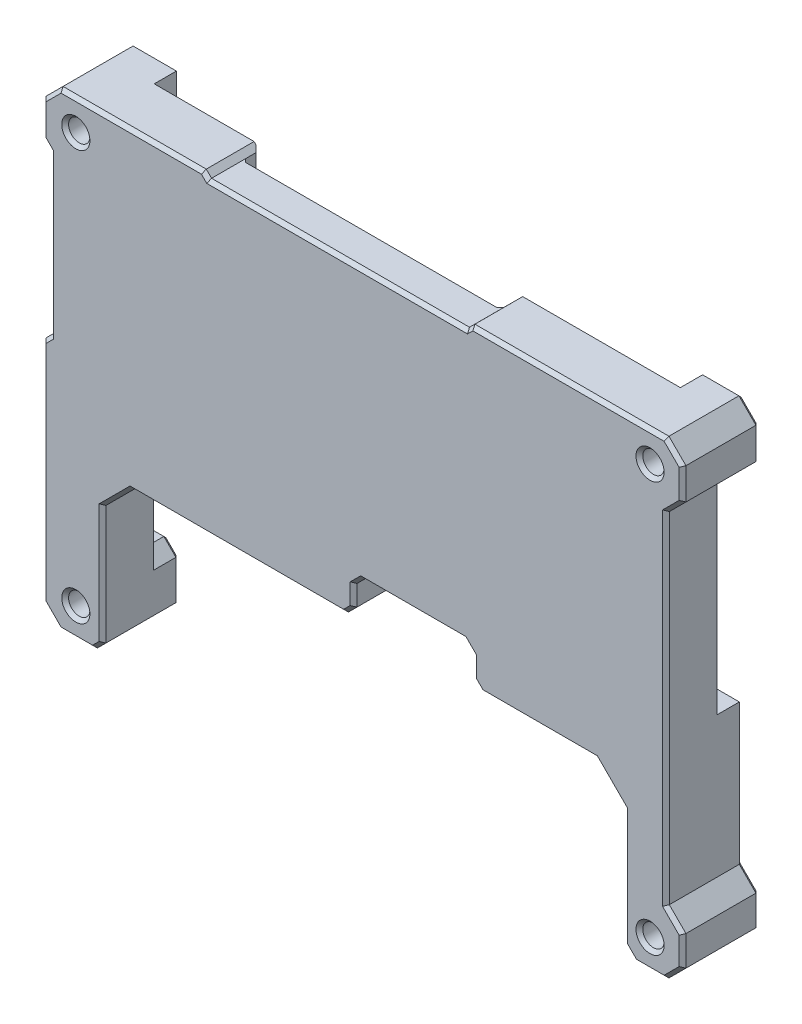
SolidWorks part; units mm, degrees
ref_plane "前视基准面" through (0, 0, 0) normal (0, 0, 1) x (1, 0, 0)
ref_plane "上视基准面" through (0, 0, 0) normal (0, 1, 0) x (1, 0, 0)
ref_plane "右视基准面" through (0, 0, 0) normal (1, 0, 0) x (0, 0, -1)
other "Configuration Table"
sketch "草图1" plane through (0, 0, 0) normal (0, 0, 1) x (1, 0, 0)
  line L1 (0, 0) -> (85, 0)
  line L2 (0, 0) -> (0, 65)
  line L3 (0, 65) -> (85, 65)
  line L4 (85, 0) -> (85, 65)
  dimension "D1" = 65
  dimension "D2" = 85
extrude "凸台-拉伸1" add sketch "草图1" along normal blind 10
sketch "草图2" plane through (0, 0, 0) normal (0, 0, -1) x (-1, 0, 0)
  circle A0 centre (-76.1669, 56.4425) radius 1.25
  circle A1 centre (-8.8888, 56.4425) radius 1.25
  circle A2 centre (-76.1669, 8.4151) radius 1.25
  circle A3 centre (-8.8888, 8.4151) radius 1.25
  dimension "D1" = 2.5
  dimension "D2" = 2.5
  dimension "D3" = 2.5
  dimension "D4" = 2.5
extrude "切除-拉伸1" cut sketch "草图2" against normal up to next
sketch "草图3" plane through (0, 0, 0) normal (0, 0, -1) x (-1, 0, 0)
  line L28 (-85, 0) -> (-85, 65) construction
  line L29 (-85, 65) -> (0, 65)
  line L30 (-85, 65) -> (-85, 0)
  line L31 (-85, 0) -> (0, 0)
  line L32 (0, 65) -> (0, 0)
  line L56 (-5, 33.4629) -> (-5.8713, 34.3342)
  line L57 (-5, 6.9926) -> (-5, 33.4629)
  line L58 (-6.9926, 5) -> (-5, 6.9926)
  line L59 (-16.2697, 5) -> (-6.9926, 5)
  line L60 (-17.4616, 6.1866) -> (-16.2697, 5)
  line L61 (-31.7436, 6.1829) -> (-17.4616, 6.1866)
  line L62 (-32.9265, 5) -> (-31.7436, 6.1829)
  line L63 (-58.7727, 5) -> (-32.9265, 5)
  line L64 (-60.0435, 6.2655) -> (-58.7727, 5)
  line L65 (-73.1524, 6.2618) -> (-60.0435, 6.2655)
  line L66 (-74.4142, 5) -> (-73.1524, 6.2618)
  line L67 (-77.9822, 5) -> (-74.4142, 5)
  line L68 (-79.9747, 6.9926) -> (-77.9822, 5)
  line L69 (-79.9747, 10.5083) -> (-79.9747, 6.9926)
  line L70 (-78.0283, 12.46) -> (-79.9747, 10.5083)
  line L71 (-78.032, 52.3531) -> (-78.0283, 12.46)
  line L72 (-79.9747, 54.2958) -> (-78.032, 52.3531)
  line L73 (-79.9747, 57.9821) -> (-79.9747, 54.2958)
  line L74 (-77.9822, 59.9747) -> (-79.9747, 57.9821)
  line L75 (-55.2451, 59.9747) -> (-77.9822, 59.9747)
  line L76 (-54.6148, 59.3497) -> (-55.2451, 59.9747)
  line L77 (-24.3949, 59.3534) -> (-54.6148, 59.3497)
  line L78 (-23.7736, 59.9747) -> (-24.3949, 59.3534)
  line L79 (-6.9926, 59.9747) -> (-23.7736, 59.9747)
  line L80 (-5, 57.9821) -> (-6.9926, 59.9747)
  line L81 (-5, 54.0174) -> (-5, 57.9821)
  line L82 (-5.875, 53.1371) -> (-5, 54.0174)
  line L83 (-5.8713, 34.3342) -> (-5.875, 53.1371)
extrude "切除-拉伸2" cut sketch "草图3" against normal up to next
sketch "草图4" plane through (0, 0, 0) normal (0, 0, -1) x (-1, 0, 0)
  line L0 (-73.1524, 6.2618) -> (-73.1524, 20.0323)
  line L1 (-73.1524, 20.0323) -> (-69.8316, 23.3532)
  line L2 (-69.8316, 23.3532) -> (-46.788, 23.3532)
  line L3 (-46.788, 23.3532) -> (-15.4038, 23.3532)
  line L4 (-15.4038, 23.3532) -> (-12.014, 19.9634)
  line L5 (-12.014, 19.9634) -> (-12.014, 6.188)
  line L6 (-31.7436, 6.1829) -> (-17.4616, 6.1866) construction
  line L7 (-12.014, 6.188) -> (-12.014, 0.194)
  line L8 (-12.014, 0.194) -> (-73.1524, 0.194)
  line L9 (-73.1524, 0.194) -> (-73.1524, 6.2618)
  line L10 (-73.1524, 6.2618) -> (-60.0435, 6.2655) construction
  dimension "D1" = 135
  dimension "D2" = 135
  dimension "D3" = 4.7938
extrude "切除-拉伸4" cut sketch "草图4" against normal up to next
sketch "草图5" plane through (0, 0, 0) normal (0, 0, -1) x (-1, 0, 0)
  line L0 (-24.3949, 59.3534) -> (-24.3949, 53.9064)
  line L1 (-24.3949, 53.9064) -> (-25.5261, 52.7749)
  line L2 (-25.5261, 52.7749) -> (-53.4826, 52.7749)
  line L3 (-53.4826, 52.7749) -> (-54.6142, 53.9061)
  line L4 (-54.6142, 53.9061) -> (-54.6148, 59.3497)
  line L5 (-24.3949, 59.3534) -> (-54.6148, 59.3497) construction
  line L6 (-23.7736, 59.9747) -> (-24.3949, 59.3534) construction
  line L7 (-24.3949, 59.3534) -> (-54.6148, 59.3497)
  dimension "D1" = 135
  dimension "D2" = 134.993
  dimension "D3" = 1.6
  dimension "D4" = 1.6
extrude "切除-拉伸7" cut sketch "草图5" against normal blind 6
sketch "草图6" plane through (0, 0, 0) normal (0, 0, -1) x (-1, 0, 0)
  line L0 (-5.8713, 34.3342) -> (-11.6713, 34.3342)
  line L1 (-5, 33.4629) -> (-5.8713, 34.3342) construction
  line L6 (-5.8713, 34.3342) -> (-5.875, 53.1371) construction
  line L7 (-5.8735, 45.2504) -> (-5.8745, 50.3342)
  line L8 (-5.8735, 45.2504) -> (-5.8713, 34.3342)
  line L9 (-5.8745, 50.3342) -> (-11.6713, 50.3342)
  line L10 (-11.6713, 50.3342) -> (-11.6713, 34.3342)
  dimension "D1" = 5.8
  dimension "D2" = 16
extrude "切除-拉伸8" cut sketch "草图6" against normal blind 6
sketch "草图7" plane through (0, 0, 0) normal (0, 0, -1) x (-1, 0, 0)
  line L0 (-76.4321, 51.2623) -> (-74.4321, 51.2623)
  line L1 (-74.4321, 51.2623) -> (-71.3195, 54.3749)
  line L2 (-71.3195, 54.3749) -> (-71.3195, 58.3749)
  line L3 (-71.3195, 58.3749) -> (-71.3195, 59.9747)
  line L4 (-76.4321, 51.2623) -> (-78.0319, 51.2623)
  line L5 (-78.0298, 28.9377) -> (-75.0298, 28.9377)
  line L6 (-75.0298, 28.9377) -> (-75.0298, 13.9377)
  line L7 (-72.9158, 11.8236) -> (-75.0298, 13.9377)
  line L8 (-24.3949, 57.6633) -> (-23.7321, 57.6633)
  line L9 (-23.7321, 57.6633) -> (-23.0617, 58.334)
  line L10 (-23.0617, 58.334) -> (-12.072, 58.334)
  line L11 (-12.072, 58.334) -> (-12.072, 55.334)
  line L12 (-12.072, 55.334) -> (-9.875, 53.1371)
  line L13 (-9.875, 53.1371) -> (-5.875, 53.1371)
  line L14 (-6.5998, 12.014) -> (-10.5998, 12.014)
  line L15 (-10.5998, 12.014) -> (-12.014, 10.5998)
  line L16 (-12.014, 10.5998) -> (-12.014, 5)
  line L17 (-6.5998, 12.014) -> (-5, 12.014)
  line L18 (-72.9158, 11.8236) -> (-73.1524, 12.0603)
  line L37 (-5.8713, 34.3342) -> (-11.6713, 34.3342)
  line L38 (-11.6713, 34.3342) -> (-11.6713, 50.3342)
  line L39 (-11.6713, 34.3342) -> (-11.6713, 50.3342)
  line L40 (-11.6713, 50.3342) -> (-5.8745, 50.3342)
  line L41 (-11.6713, 50.3342) -> (-5.8745, 50.3342)
  line L42 (-5.8745, 50.3342) -> (-5.875, 53.1371)
  line L43 (-5.875, 53.1371) -> (-5, 54.0174)
  line L44 (-5, 54.0174) -> (-5, 57.9821)
  line L45 (-5, 57.9821) -> (-6.9926, 59.9747)
  line L46 (-6.9926, 59.9747) -> (-23.7736, 59.9747)
  line L47 (-23.7736, 59.9747) -> (-24.3949, 59.3534)
  line L48 (-24.3949, 59.3534) -> (-24.3949, 53.9064)
  line L49 (-24.3949, 53.9064) -> (-25.5261, 52.7749)
  line L50 (-25.5261, 52.7749) -> (-53.4826, 52.7749)
  line L51 (-53.4826, 52.7749) -> (-54.6142, 53.9061)
  line L52 (-54.6142, 53.9061) -> (-54.6148, 59.3497)
  line L53 (-54.6148, 59.3497) -> (-55.2451, 59.9747)
  line L54 (-55.2451, 59.9747) -> (-77.9822, 59.9747)
  line L55 (-77.9822, 59.9747) -> (-79.9747, 57.9821)
  line L56 (-79.9747, 57.9821) -> (-79.9747, 54.2958)
  line L57 (-79.9747, 54.2958) -> (-78.032, 52.3531)
  line L58 (-78.032, 52.3531) -> (-78.0283, 12.46)
  line L59 (-78.0283, 12.46) -> (-79.9747, 10.5083)
  line L60 (-79.9747, 10.5083) -> (-79.9747, 6.9926)
  line L61 (-79.9747, 6.9926) -> (-77.9822, 5)
  line L62 (-77.9822, 5) -> (-74.4142, 5)
  line L63 (-74.4142, 5) -> (-73.1524, 6.2618)
  line L64 (-73.1524, 6.2618) -> (-73.1524, 20.0323)
  line L65 (-73.1524, 20.0323) -> (-69.8316, 23.3532)
  line L66 (-69.8316, 23.3532) -> (-15.4038, 23.3532)
  line L67 (-15.4038, 23.3532) -> (-12.014, 19.9634)
  line L68 (-12.014, 19.9634) -> (-12.014, 5)
  line L70 (-12.014, 5) -> (-6.9926, 5)
  line L71 (-6.9926, 5) -> (-5, 6.9926)
  line L72 (-5, 6.9926) -> (-5, 33.4629)
  line L73 (-5, 33.4629) -> (-5.8713, 34.3342)
  line L74 (-5.8713, 34.3342) -> (-11.6713, 34.3342)
  line L79 (-5.8745, 50.3342) -> (-5.875, 53.1371)
  line L80 (-5.875, 53.1371) -> (-5, 54.0174)
  line L81 (-5, 54.0174) -> (-5, 57.9821)
  line L82 (-5, 57.9821) -> (-6.9926, 59.9747)
  line L83 (-6.9926, 59.9747) -> (-23.7736, 59.9747)
  line L84 (-23.7736, 59.9747) -> (-24.3949, 59.3534)
  line L85 (-24.3949, 59.3534) -> (-24.3949, 53.9064)
  line L86 (-24.3949, 53.9064) -> (-25.5261, 52.7749)
  line L87 (-25.5261, 52.7749) -> (-53.4826, 52.7749)
  line L88 (-53.4826, 52.7749) -> (-54.6142, 53.9061)
  line L89 (-54.6142, 53.9061) -> (-54.6148, 59.3497)
  line L90 (-54.6148, 59.3497) -> (-55.2451, 59.9747)
  line L91 (-55.2451, 59.9747) -> (-77.9822, 59.9747)
  line L92 (-77.9822, 59.9747) -> (-79.9747, 57.9821)
  line L93 (-79.9747, 57.9821) -> (-79.9747, 54.2958)
  line L94 (-79.9747, 54.2958) -> (-78.032, 52.3531)
  line L95 (-78.032, 52.3531) -> (-78.0283, 12.46)
  line L96 (-78.0283, 12.46) -> (-79.9747, 10.5083)
  line L97 (-79.9747, 10.5083) -> (-79.9747, 6.9926)
  line L98 (-79.9747, 6.9926) -> (-77.9822, 5)
  line L99 (-77.9822, 5) -> (-74.4142, 5)
  line L100 (-74.4142, 5) -> (-73.1524, 6.2618)
  line L101 (-73.1524, 6.2618) -> (-73.1524, 20.0323)
  line L102 (-73.1524, 20.0323) -> (-69.8316, 23.3532)
  line L103 (-69.8316, 23.3532) -> (-15.4038, 23.3532)
  line L104 (-15.4038, 23.3532) -> (-12.014, 19.9634)
  line L105 (-12.014, 19.9634) -> (-12.014, 5)
  line L107 (-12.014, 5) -> (-6.9926, 5)
  line L108 (-6.9926, 5) -> (-5, 6.9926)
  line L109 (-5, 6.9926) -> (-5, 33.4629)
  line L110 (-5, 33.4629) -> (-5.8713, 34.3342)
  dimension "D2" = 90
  dimension "D3" = 15
  dimension "D4" = 135
  dimension "D5" = 4
  dimension "D6" = 3
  dimension "D7" = 135
  dimension "D8" = 45
  dimension "D9" = 3
  dimension "D1" = 0
extrude "切除-拉伸11" cut sketch "草图7" against normal blind 4
sketch "草图8" plane through (0, 0, 4) normal (0, 0, -1) x (-1, 0, 0)
  line L1 (-73.3481, 45.9587) -> (-65.3481, 45.9587)
  line L2 (-73.3481, 45.9587) -> (-73.3481, 40.9587)
  line L3 (-73.3481, 40.9587) -> (-65.3481, 40.9587)
  line L4 (-65.3481, 45.9587) -> (-65.3481, 40.9587)
  dimension "D1" = 5
  dimension "D2" = 8
extrude "切除-拉伸12" cut sketch "草图8" against normal blind 1
sketch "草图10" plane through (0, 0, 4) normal (0, 0, -1) x (-1, 0, 0)
  line L0 (-41.5465, 34.8898) -> (-37.5465, 34.8898)
  line L1 (-46.9465, 34.8898) -> (-41.5465, 34.8898)
  line L2 (-46.9465, 34.8898) -> (-46.9465, 28.8898)
  line L3 (-46.9465, 28.8898) -> (-41.5465, 28.8898)
  line L4 (-41.5465, 34.8898) -> (-41.5465, 28.8898)
  line L5 (-37.5465, 34.8898) -> (-32.1465, 34.8898)
  line L6 (-37.5465, 34.8898) -> (-37.5465, 28.8898)
  line L7 (-37.5465, 28.8898) -> (-32.1465, 28.8898)
  line L8 (-32.1465, 34.8898) -> (-32.1465, 28.8898)
  line L9 (-37.5465, 28.8898) -> (-41.5465, 28.8898)
  dimension "D1" = 5.4
  dimension "D2" = 6
  dimension "D3" = 5.4
  dimension "D4" = 4
extrude "凸台-拉伸2" add sketch "草图10" along normal offset from surface (2.04 mm away) 3 contours L4 L1 L2 L3 | L9 L6 L0 L4 | L8 L5 L6 L7
sketch "草图11" plane through (0, 0, 4) normal (0, 0, -1) x (-1, 0, 0)
  line L1 (-40.8318, 43.6929) -> (-36.6318, 43.6929)
  line L2 (-40.8318, 43.6929) -> (-40.8318, 38.6929)
  line L3 (-40.8318, 38.6929) -> (-36.6318, 38.6929)
  line L4 (-36.6318, 43.6929) -> (-36.6318, 38.6929)
  dimension "D1" = 4.2
  dimension "D2" = 5
extrude "凸台-拉伸3" add sketch "草图11" along normal offset from surface (1.3001 mm away) 3
sketch "草图12" plane through (0, 0, 4) normal (0, 0, -1) x (-1, 0, 0)
  line L0 (-24.6106, 30.6859) -> (-32.1465, 34.8898)
  line L1 (-30.6106, 30.6859) -> (-18.6106, 30.6859)
  line L2 (-30.6106, 30.6859) -> (-30.6106, 24.6859)
  line L3 (-30.6106, 24.6859) -> (-18.6106, 24.6859)
  line L4 (-18.6106, 30.6859) -> (-18.6106, 24.6859)
  line L5 (-32.1465, 34.8898) -> (-46.9465, 34.8898) construction
  line L6 (-32.1465, 28.8898) -> (-32.1465, 34.8898) construction
  line L7 (-32.1465, 34.8898) -> (-32.1465, 28.8898)
  line L8 (-32.1465, 28.8898) -> (-30.6106, 27.6859)
  line M47 (-32.1465, 34.8898) -> (-32.1465, 28.8898)
  dimension "D1" = 12
  dimension "D2" = 6
extrude "凸台-拉伸4" add sketch "草图12" along normal up to surface (2.04 mm away) contours L4 L1 L2 L3 | L8 L2 L1 L0 M47 up to face at (39.5465, 31.8898, 1.96)
sketch "草图13" plane through (0, 0, 4) normal (0, 0, -1) x (-1, 0, 0)
  line L1 (-62.8902, 40.6188) -> (-59.7758, 40.6188)
  line L2 (-62.8902, 40.6188) -> (-62.8902, 35.6362)
  line L3 (-62.8902, 35.6362) -> (-59.7758, 35.6362)
  line L4 (-59.7758, 40.6188) -> (-59.7758, 35.6362)
extrude "凸台-拉伸5" add sketch "草图13" along normal blind 2
sketch "草图15" plane through (0, 0, 10) normal (0, 0, 1) x (1, 0, 0)
  line L0 (69.8316, 23.3532) -> (15.4038, 23.3532) construction
  line L1 (41.4288, 23.3532) -> (55.4288, 23.3532)
  line L2 (41.4288, 23.3532) -> (41.4288, 27.7532)
  line L3 (41.4288, 27.7532) -> (55.4288, 27.7532)
  line L4 (55.4288, 23.3532) -> (55.4288, 27.7532)
  dimension "D1" = 14
  dimension "D2" = 4.4
extrude "切除-拉伸13" cut sketch "草图15" against normal up to surface (6 mm away) up to face at (69.3481, 43.4587, 4)
chamfer "倒角1" distance 1 angle 45 5 edges at (12.014, 5, 5) (55.4288, 23.3532, 7) (55.4288, 27.7532, 7) (41.4288, 27.7532, 7) (41.4288, 23.3532, 7)
chamfer "倒角2" distance 0.6 angle 45 4 edges at (59.7758, 38.1275, 4) (61.333, 40.6188, 4) (62.8902, 38.1275, 4) (61.333, 35.6362, 4)
chamfer "倒角5" distance 0.6 angle 45 4 edges at (36.6318, 41.1929, 4) (38.7318, 38.6929, 4) (40.8318, 41.1929, 4) (38.7318, 43.6929, 4)
sketch "草图16" plane through (0, 0, 4) normal (0, 0, -1) x (-1, 0, 0)
  circle A0 centre (-17.8941, 26.9463) radius 1.6
  dimension "D1" = 3.2
extrude "切除-拉伸14" [suppressed] cut sketch "草图16" against normal through all both and the other way through all
sketch "草图17" plane through (0, 0, 0) normal (0, 0, -1) x (-1, 0, 0)
  line L0 (-12.072, 58.334) -> (-12.072, 59.9747)
  line L2 (-6.9926, 59.9747) -> (-23.7736, 59.9747) construction
  line L15 (-24.3949, 59.3534) -> (-24.3949, 57.6633)
  line L16 (-24.3949, 57.6633) -> (-23.7321, 57.6633)
  line L17 (-23.7321, 57.6633) -> (-23.0617, 58.334)
  line L18 (-23.0617, 58.334) -> (-12.072, 58.334)
  line L19 (-12.072, 58.334) -> (-12.072, 55.334)
  line L20 (-12.072, 55.334) -> (-9.875, 53.1371)
  line L21 (-9.875, 53.1371) -> (-5.875, 53.1371)
  line L22 (-5.875, 53.1371) -> (-5, 54.0174)
  line L23 (-5, 54.0174) -> (-5, 57.9821)
  line L24 (-5, 57.9821) -> (-6.9926, 59.9747)
  line L25 (-6.9926, 59.9747) -> (-23.7736, 59.9747)
  line L26 (-23.7736, 59.9747) -> (-24.3949, 59.3534)
  line L27 (-24.3949, 59.3534) -> (-24.3949, 57.6633)
  line L28 (-24.3949, 57.6633) -> (-23.7321, 57.6633)
  line L29 (-23.7321, 57.6633) -> (-23.0617, 58.334)
  line L30 (-23.0617, 58.334) -> (-12.072, 58.334)
  line L31 (-12.072, 58.334) -> (-12.072, 55.334)
  line L32 (-12.072, 55.334) -> (-9.875, 53.1371)
  line L33 (-9.875, 53.1371) -> (-5.875, 53.1371)
  line L34 (-5.875, 53.1371) -> (-5, 54.0174)
  line L35 (-5, 54.0174) -> (-5, 57.9821)
  line L36 (-5, 57.9821) -> (-6.9926, 59.9747)
  line L37 (-6.9926, 59.9747) -> (-23.7736, 59.9747)
  line L38 (-23.7736, 59.9747) -> (-24.3949, 59.3534)
  line M15 (-24.3949, 59.3534) -> (-24.3949, 57.6633)
  line M16 (-24.3949, 57.6633) -> (-23.7321, 57.6633)
  line M17 (-23.7321, 57.6633) -> (-23.0617, 58.334)
  line M18 (-23.0617, 58.334) -> (-12.072, 58.334)
  line M25 (-6.9926, 59.9747) -> (-23.7736, 59.9747)
  line M26 (-23.7736, 59.9747) -> (-24.3949, 59.3534)
  dimension "D1" = 0
extrude "切除-拉伸15" cut sketch "草图17" against normal up to surface (4 mm away) contours L0 M18 M25 M26 M15 M16 M17 up to face at (38.7318, 41.1929, 4)
sketch "草图18" plane through (0, 0, 0) normal (0, 0, -1) x (-1, 0, 0)
  line L0 (-73.7195, 59.9747) -> (-73.7195, 54.0502)
  line L1 (-71.3195, 59.9747) -> (-77.9822, 59.9747) construction
  line L2 (-73.7195, 54.0502) -> (-75.4166, 52.3531)
  line L3 (-75.4166, 52.3531) -> (-78.032, 52.3531)
  line L12 (-78.032, 52.3531) -> (-78.0319, 51.2623)
  line L13 (-78.0319, 51.2623) -> (-74.4321, 51.2623)
  line L14 (-74.4321, 51.2623) -> (-71.3195, 54.3749)
  line L15 (-71.3195, 54.3749) -> (-71.3195, 59.9747)
  line L16 (-71.3195, 59.9747) -> (-77.9822, 59.9747)
  line L17 (-77.9822, 59.9747) -> (-79.9747, 57.9821)
  line L18 (-79.9747, 57.9821) -> (-79.9747, 54.2958)
  line L19 (-79.9747, 54.2958) -> (-78.032, 52.3531)
  line L20 (-78.032, 52.3531) -> (-78.0319, 51.2623)
  line L21 (-78.0319, 51.2623) -> (-74.4321, 51.2623)
  line L22 (-74.4321, 51.2623) -> (-71.3195, 54.3749)
  line L23 (-71.3195, 54.3749) -> (-71.3195, 59.9747)
  line L24 (-71.3195, 59.9747) -> (-77.9822, 59.9747)
  line L25 (-77.9822, 59.9747) -> (-79.9747, 57.9821)
  line L26 (-79.9747, 57.9821) -> (-79.9747, 54.2958)
  line L27 (-79.9747, 54.2958) -> (-78.032, 52.3531)
  line M13 (-78.032, 52.3531) -> (-78.0319, 51.2623)
  line M14 (-78.0319, 51.2623) -> (-74.4321, 51.2623)
  line M15 (-74.4321, 51.2623) -> (-71.3195, 54.3749)
  line M16 (-71.3195, 54.3749) -> (-71.3195, 59.9747)
  line M17 (-71.3195, 59.9747) -> (-77.9822, 59.9747)
  dimension "D1" = 0
  dimension "D2" = 2.4
  dimension "D3" = 2.4
extrude "切除-拉伸16" cut sketch "草图18" against normal up to surface (4 mm away) contours L2 L3 L0 M13 M14 M15 M16 M17 up to face at (38.7318, 41.1929, 4)
chamfer "倒角6" distance 0.4 angle 45 39 edges at (5.9963, 5.9963, 10) (5, 20.2277, 10) (5.4357, 33.8986, 10) (5.8732, 43.7356, 10) (5.4375, 53.5772, 10) (5, 55.9998, 10) (5.9963, 58.9784, 10) (15.3831, 59.9747, 10) (24.0842, 59.6641, 10) (39.5048, 59.3515, 10) (54.93, 59.6622, 10) (66.6136, 59.9747, 10) (78.9785, 58.9784, 10) (79.9747, 56.139, 10) (79.0034, 53.3245, 10) (78.0302, 32.4066, 10) (79.0015, 11.4841, 10) (79.9747, 8.7504, 10) (78.9785, 5.9963, 10) (76.1982, 5, 10) (73.7833, 5.6309, 10) (73.1524, 13.1471, 10) (71.492, 21.6927, 10) (27.9163, 23.3532, 10) (55.9288, 23.8532, 10) (55.4288, 25.5532, 10) (54.9288, 27.2532, 10) (48.4288, 27.7532, 10) (41.9288, 27.2532, 10) (41.4288, 25.5532, 10) (40.9288, 23.8532, 10) (13.7089, 21.6583, 10) (12.014, 12.9817, 10) (11.514, 5.5, 10) (9.0033, 5, 10) (7.6388, 56.4425, 10) (74.9169, 8.4151, 10) (7.6388, 8.4151, 10) (74.9169, 56.4425, 10)
chamfer "倒角8" distance 0.4 angle 45 8 edges at (8.7729, 50.3342, 6) (11.6713, 50.3342, 5) (11.6713, 42.3342, 6) (8.7713, 34.3342, 6) (11.6713, 34.3342, 5) (8.7729, 50.3342, 4) (11.6713, 42.3342, 4) (8.7713, 34.3342, 4)
chamfer "倒角9" distance 0.4 angle 45 10 edges at (54.6145, 56.6279, 4) (54.6145, 56.6279, 6) (54.0484, 53.3405, 4) (54.0484, 53.3405, 6) (24.3949, 56.6299, 4) (24.3949, 56.6299, 6) (24.9605, 53.3407, 4) (24.9605, 53.3407, 6) (39.5044, 52.7749, 4) (39.5044, 52.7749, 6)
sketch "草图19" plane through (0, 0, 4) normal (0, 0, -1) x (-1, 0, 0)
  line L1 (-67.6316, 31.7532) -> (-58.2316, 31.7532)
  line L2 (-67.6316, 31.7532) -> (-67.6316, 23.3532)
  line L3 (-67.6316, 23.3532) -> (-58.2316, 23.3532)
  line L4 (-58.2316, 31.7532) -> (-58.2316, 23.3532)
  line L5 (-69.8316, 23.3532) -> (-56.4288, 23.3532) construction
  dimension "D1" = 9.4
  dimension "D2" = 8.4
  dimension "D3" = 2.2
extrude "切除-拉伸17" cut sketch "草图19" against normal blind 2.4
chamfer "倒角12" distance 0.4 angle 45 11 edges at (67.6316, 27.5532, 6.4) (67.6316, 23.3532, 5.2) (62.9316, 31.7532, 6.4) (67.6316, 31.7532, 5.2) (58.2316, 27.5532, 6.4) (58.2316, 31.7532, 5.2) (62.9316, 23.3532, 6.4) (58.2316, 23.3532, 5.2) (67.6316, 27.5532, 4) (58.2316, 27.5532, 4) (62.9316, 31.7532, 4)
chamfer "倒角13" [suppressed] distance 0.4
chamfer "倒角15" distance 0.4 angle 45 9 edges at (46.9465, 31.8898, 4) (39.5465, 34.8898, 4) (28.3786, 32.7879, 4) (21.6106, 30.6859, 4) (18.6106, 27.6859, 4) (24.6106, 24.6859, 4) (30.6106, 26.1859, 4) (31.3786, 28.2879, 4) (39.5465, 28.8898, 4)
sketch "草图20" plane through (0, 0, 0) normal (0, 0, -1) x (-1, 0, 0)
  line L0 (-6.9926, 59.9747) -> (-12.072, 59.9747) construction
  line L1 (-12.072, 59.9747) -> (-12.072, 55.334) construction
  line L2 (-12.072, 55.334) -> (-9.875, 53.1371) construction
  line L3 (-9.875, 53.1371) -> (-5.875, 53.1371) construction
  line L4 (-5.875, 53.1371) -> (-5, 54.0174) construction
  line L5 (-5, 54.0174) -> (-5, 57.9821) construction
  line L6 (-5, 57.9821) -> (-6.9926, 59.9747) construction
  line L7 (-73.7195, 54.0502) -> (-73.7195, 59.9747) construction
  line L8 (-73.7195, 59.9747) -> (-77.9822, 59.9747) construction
  line L9 (-77.9822, 59.9747) -> (-79.9747, 57.9821) construction
  line L10 (-79.9747, 57.9821) -> (-79.9747, 54.2958) construction
  line L11 (-79.9747, 54.2958) -> (-78.032, 52.3531) construction
  line L12 (-78.032, 52.3531) -> (-75.4166, 52.3531) construction
  line L13 (-75.4166, 52.3531) -> (-73.7195, 54.0502) construction
  line L14 (-73.1524, 6.2618) -> (-73.1524, 12.0603) construction
  line L15 (-73.1524, 12.0603) -> (-75.0298, 13.9377) construction
  line L16 (-75.0298, 13.9377) -> (-75.0298, 28.9377) construction
  line L17 (-75.0298, 28.9377) -> (-78.0298, 28.9377) construction
  line L18 (-78.0298, 28.9377) -> (-78.0283, 12.46) construction
  line L19 (-78.0283, 12.46) -> (-79.9747, 10.5083) construction
  line L20 (-79.9747, 10.5083) -> (-79.9747, 6.9926) construction
  line L21 (-79.9747, 6.9926) -> (-77.9822, 5) construction
  line L22 (-77.9822, 5) -> (-74.4142, 5) construction
  line L23 (-74.4142, 5) -> (-73.1524, 6.2618) construction
  line L24 (-12.014, 10.5998) -> (-12.014, 6) construction
  line L25 (-12.014, 6) -> (-11.014, 5) construction
  line L26 (-11.014, 5) -> (-6.9926, 5) construction
  line L27 (-6.9926, 5) -> (-5, 6.9926) construction
  line L28 (-5, 6.9926) -> (-5, 12.014) construction
  line L29 (-5, 12.014) -> (-10.5998, 12.014) construction
  line L30 (-10.5998, 12.014) -> (-12.014, 10.5998) construction
  line L31 (-6.9926, 59.9747) -> (-12.072, 59.9747)
  line L32 (-12.072, 59.9747) -> (-12.072, 55.334)
  line L33 (-12.072, 55.334) -> (-9.875, 53.1371)
  line L34 (-9.875, 53.1371) -> (-5.875, 53.1371)
  line L35 (-5.875, 53.1371) -> (-5, 54.0174)
  line L36 (-5, 54.0174) -> (-5, 57.9821)
  line L37 (-5, 57.9821) -> (-6.9926, 59.9747)
  line L38 (-73.7195, 54.0502) -> (-73.7195, 59.9747)
  line L39 (-73.7195, 59.9747) -> (-77.9822, 59.9747)
  line L40 (-77.9822, 59.9747) -> (-79.9747, 57.9821)
  line L41 (-79.9747, 57.9821) -> (-79.9747, 54.2958)
  line L42 (-79.9747, 54.2958) -> (-78.032, 52.3531)
  line L43 (-78.032, 52.3531) -> (-75.4166, 52.3531)
  line L44 (-75.4166, 52.3531) -> (-73.7195, 54.0502)
  line L45 (-73.1524, 6.2618) -> (-73.1524, 12.0603)
  line L46 (-73.1524, 12.0603) -> (-75.0298, 13.9377)
  line L47 (-75.0298, 13.9377) -> (-75.0298, 28.9377)
  line L48 (-75.0298, 28.9377) -> (-78.0298, 28.9377)
  line L49 (-78.0298, 28.9377) -> (-78.0283, 12.46)
  line L50 (-78.0283, 12.46) -> (-79.9747, 10.5083)
  line L51 (-79.9747, 10.5083) -> (-79.9747, 6.9926)
  line L52 (-79.9747, 6.9926) -> (-77.9822, 5)
  line L53 (-77.9822, 5) -> (-74.4142, 5)
  line L54 (-74.4142, 5) -> (-73.1524, 6.2618)
  line L55 (-12.014, 10.5998) -> (-12.014, 6)
  line L56 (-12.014, 6) -> (-11.014, 5)
  line L57 (-11.014, 5) -> (-6.9926, 5)
  line L58 (-6.9926, 5) -> (-5, 6.9926)
  line L59 (-5, 6.9926) -> (-5, 12.014)
  line L60 (-5, 12.014) -> (-10.5998, 12.014)
  line L61 (-10.5998, 12.014) -> (-12.014, 10.5998)
  line L62 (-6.9926, 59.9747) -> (-12.072, 59.9747)
  line L63 (-12.072, 59.9747) -> (-12.072, 55.334)
  line L64 (-12.072, 55.334) -> (-9.875, 53.1371)
  line L65 (-9.875, 53.1371) -> (-5.875, 53.1371)
  line L66 (-5.875, 53.1371) -> (-5, 54.0174)
  line L67 (-5, 54.0174) -> (-5, 57.9821)
  line L68 (-5, 57.9821) -> (-6.9926, 59.9747)
  line L69 (-12.014, 10.5998) -> (-12.014, 6)
  line L70 (-12.014, 6) -> (-11.014, 5)
  line L71 (-11.014, 5) -> (-6.9926, 5)
  line L72 (-6.9926, 5) -> (-5, 6.9926)
  line L73 (-5, 6.9926) -> (-5, 12.014)
  line L74 (-5, 12.014) -> (-10.5998, 12.014)
  line L75 (-10.5998, 12.014) -> (-12.014, 10.5998)
  line L76 (-73.1524, 6.2618) -> (-73.1524, 12.0603)
  line L77 (-73.1524, 12.0603) -> (-75.0298, 13.9377)
  line L78 (-75.0298, 13.9377) -> (-75.0298, 28.9377)
  line L79 (-75.0298, 28.9377) -> (-78.0298, 28.9377)
  line L80 (-78.0298, 28.9377) -> (-78.0283, 12.46)
  line L81 (-78.0283, 12.46) -> (-79.9747, 10.5083)
  line L82 (-79.9747, 10.5083) -> (-79.9747, 6.9926)
  line L83 (-79.9747, 6.9926) -> (-77.9822, 5)
  line L84 (-77.9822, 5) -> (-74.4142, 5)
  line L85 (-74.4142, 5) -> (-73.1524, 6.2618)
  line L86 (-73.7195, 54.0502) -> (-73.7195, 59.9747)
  line L87 (-73.7195, 59.9747) -> (-77.9822, 59.9747)
  line L88 (-77.9822, 59.9747) -> (-79.9747, 57.9821)
  line L89 (-79.9747, 57.9821) -> (-79.9747, 54.2958)
  line L90 (-79.9747, 54.2958) -> (-78.032, 52.3531)
  line L91 (-78.032, 52.3531) -> (-75.4166, 52.3531)
  line L92 (-75.4166, 52.3531) -> (-73.7195, 54.0502)
  circle A1 centre (-76.1669, 8.4151) radius 1.25
  circle A2 centre (-76.1669, 8.4151) radius 1.25
  circle A3 centre (-76.1669, 56.4425) radius 1.25
  circle A4 centre (-76.1669, 56.4425) radius 1.25
  circle A5 centre (-8.8888, 56.4425) radius 1.25
  circle A6 centre (-8.8888, 56.4425) radius 1.25
  circle A7 centre (-8.8888, 8.4151) radius 1.25
  circle A8 centre (-8.8888, 8.4151) radius 1.25
  dimension "D1" = 0
  dimension "D2" = 0
  dimension "D3" = 0
  dimension "D4" = 0
extrude "切除-拉伸18" cut sketch "草图20" against normal offset from surface (1 mm away) 9 contours L43 L44 L38 L39 L40 L41 L42 A4 | L53 L54 L45 L46 L47 L48 L49 L50 L51 L52 A2 | L36 L37 L31 L32 L33 L34 L35 A6
chamfer "倒角16" distance 0.4 angle 45 35 edges at (74.9169, 8.4151, 1) (78.9785, 5.9963, 1) (79.9747, 8.7504, 1) (79.0015, 11.4841, 1) (78.0291, 20.6989, 1) (76.5298, 28.9377, 1) (75.0298, 21.4377, 1) (74.0911, 12.999, 1) (73.1524, 9.1611, 1) (73.7833, 5.6309, 1) (76.1982, 5, 1) (7.6388, 8.4151, 1) (7.7999, 12.014, 1) (5, 9.5033, 1) (5.9963, 5.9963, 1) (9.0033, 5, 1) (11.514, 5.5, 1) (12.014, 8.2999, 1) (11.3069, 11.3069, 1) (7.6388, 56.4425, 1) (5.4375, 53.5772, 1) (7.875, 53.1371, 1) (10.9735, 54.2355, 1) (12.072, 57.6543, 1) (9.5323, 59.9747, 1) (5.9963, 58.9784, 1) (5, 55.9998, 1) (74.9169, 56.4425, 1) (79.0034, 53.3245, 1) (79.9747, 56.139, 1) (78.9785, 58.9784, 1) (75.8509, 59.9747, 1) (73.7195, 57.0124, 1) (74.568, 53.2016, 1) (76.7243, 52.3531, 1)
sketch "草图21" plane through (0, 0, 1) normal (0, 0, -1) x (-1, 0, 0)
  line L0 (-62.8902, 40.6188) -> (-62.8902, 35.6362) construction
  line L1 (-62.8902, 35.6362) -> (-59.7758, 35.6362) construction
  line L2 (-59.7758, 35.6362) -> (-59.7758, 40.6188) construction
  line L3 (-59.7758, 40.6188) -> (-62.8902, 40.6188) construction
  line L4 (-46.9465, 28.8898) -> (-32.1465, 28.8898) construction
  line L5 (-32.1465, 28.8898) -> (-30.6106, 27.6859) construction
  line L6 (-30.6106, 27.6859) -> (-30.6106, 24.6859) construction
  line L7 (-30.6106, 24.6859) -> (-18.6106, 24.6859) construction
  line L8 (-18.6106, 24.6859) -> (-18.6106, 30.6859) construction
  line L9 (-18.6106, 30.6859) -> (-24.6106, 30.6859) construction
  line L10 (-24.6106, 30.6859) -> (-32.1465, 34.8898) construction
  line L11 (-32.1465, 34.8898) -> (-46.9465, 34.8898) construction
  line L12 (-46.9465, 34.8898) -> (-46.9465, 28.8898) construction
  line L13 (-62.8902, 40.6188) -> (-62.8902, 35.6362)
  line L14 (-62.8902, 35.6362) -> (-59.7758, 35.6362)
  line L15 (-59.7758, 35.6362) -> (-59.7758, 40.6188)
  line L16 (-59.7758, 40.6188) -> (-62.8902, 40.6188)
  line L17 (-46.9465, 28.8898) -> (-32.1465, 28.8898)
  line L18 (-32.1465, 28.8898) -> (-30.6106, 27.6859)
  line L19 (-30.6106, 27.6859) -> (-30.6106, 24.6859)
  line L20 (-30.6106, 24.6859) -> (-18.6106, 24.6859)
  line L21 (-18.6106, 24.6859) -> (-18.6106, 30.6859)
  line L22 (-18.6106, 30.6859) -> (-24.6106, 30.6859)
  line L23 (-24.6106, 30.6859) -> (-32.1465, 34.8898)
  line L24 (-32.1465, 34.8898) -> (-46.9465, 34.8898)
  line L25 (-46.9465, 34.8898) -> (-46.9465, 28.8898)
  line L30 (-40.8318, 38.6929) -> (-36.6318, 38.6929)
  line L31 (-36.6318, 38.6929) -> (-36.6318, 43.6929)
  line L32 (-36.6318, 43.6929) -> (-40.8318, 43.6929)
  line L33 (-40.8318, 43.6929) -> (-40.8318, 38.6929)
  line L34 (-40.8318, 38.6929) -> (-36.6318, 38.6929)
  line L35 (-36.6318, 38.6929) -> (-36.6318, 43.6929)
  line L36 (-36.6318, 43.6929) -> (-40.8318, 43.6929)
  line L37 (-40.8318, 43.6929) -> (-40.8318, 38.6929)
  dimension "D1" = 0
extrude "凸台-拉伸6" add sketch "草图21" against normal up to surface (1.6999 mm away) up to face at (38.7318, 41.1929, 2.6999)
chamfer "倒角17" distance 0.4 angle 45 17 edges at (38.7318, 43.6929, 1) (36.6318, 41.1929, 1) (38.7318, 38.6929, 1) (40.8318, 41.1929, 1) (39.5465, 34.8898, 1) (28.3786, 32.7879, 1) (21.6106, 30.6859, 1) (18.6106, 27.6859, 1) (24.6106, 24.6859, 1) (30.6106, 26.1859, 1) (31.3786, 28.2879, 1) (39.5465, 28.8898, 1) (46.9465, 31.8898, 1) (59.7758, 38.1275, 1) (61.333, 35.6362, 1) (62.8902, 38.1275, 1) (61.333, 40.6188, 1)
sketch "草图22" plane through (0, 0, 5) normal (0, 0, -1) x (-1, 0, 0)
  line L4 (-73.3481, 45.9587) -> (-73.3481, 40.9587)
  line L5 (-73.3481, 40.9587) -> (-65.3481, 40.9587)
  line L6 (-65.3481, 40.9587) -> (-65.3481, 45.9587)
  line L7 (-65.3481, 45.9587) -> (-73.3481, 45.9587)
  line L8 (-73.3481, 45.9587) -> (-73.3481, 40.9587)
  line L9 (-73.3481, 40.9587) -> (-65.3481, 40.9587)
  line L10 (-65.3481, 40.9587) -> (-65.3481, 45.9587)
  line L11 (-65.3481, 45.9587) -> (-73.3481, 45.9587)
  dimension "D1" = 0
extrude "切除-拉伸19" cut sketch "草图22" against normal up to surface (1 mm away) up to face at (39.5046, 55.5328, 6)
chamfer "倒角18" distance 0.4 angle 45 12 edges at (69.3481, 45.9587, 4) (69.3481, 45.9587, 6) (69.3481, 40.9587, 4) (69.3481, 40.9587, 6) (65.3481, 40.9587, 5) (65.3481, 43.4587, 4) (65.3481, 43.4587, 6) (65.3481, 45.9587, 5) (73.3481, 45.9587, 5) (73.3481, 43.4587, 4) (73.3481, 43.4587, 6) (73.3481, 40.9587, 5)
